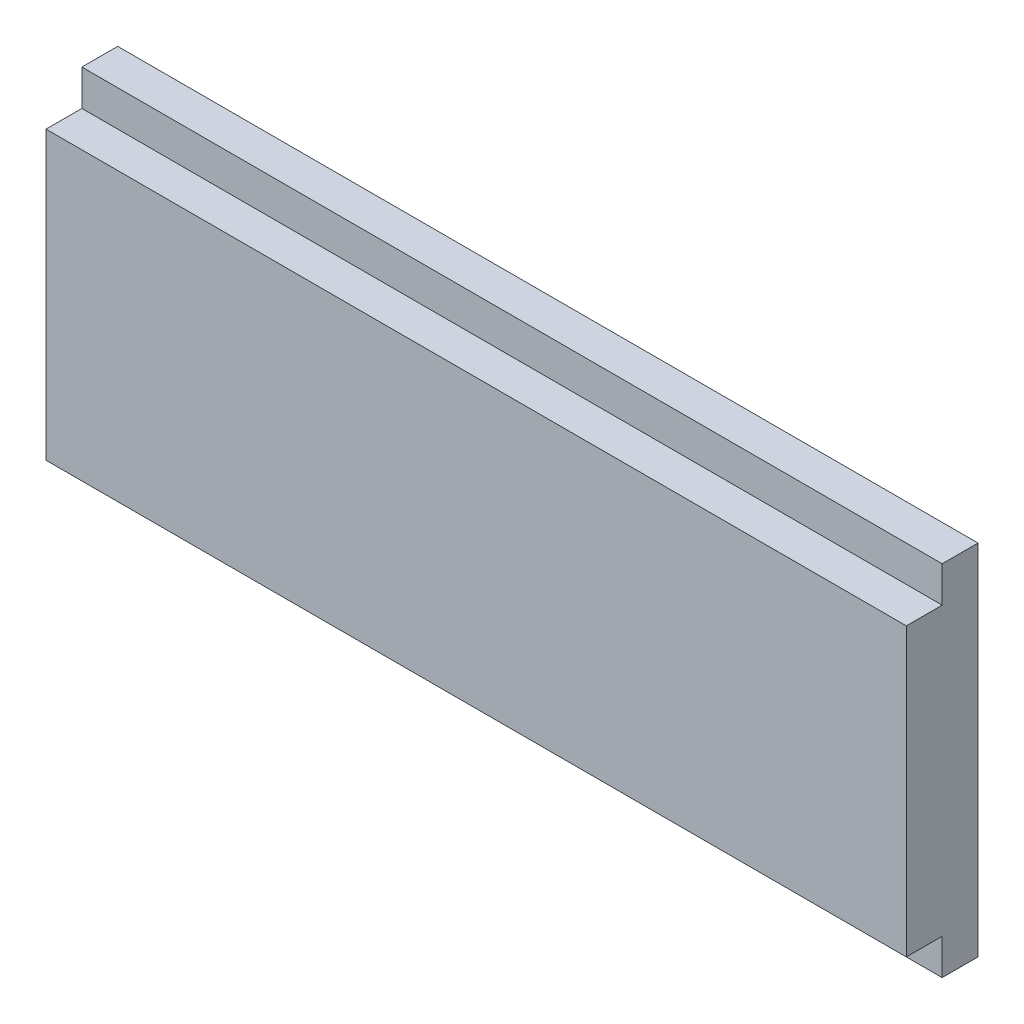
SolidWorks part; units mm, degrees
ref_plane "Спереди" through (0, 0, 0) normal (0, 0, 1) x (1, 0, 0)
ref_plane "Сверху" through (0, 0, 0) normal (0, 1, 0) x (1, 0, 0)
ref_plane "Справа" through (0, 0, 0) normal (1, 0, 0) x (0, 0, -1)
other "Configuration Table"
sketch "Эскиз1" plane through (0, 0, 0) normal (0, 0, 1) x (1, 0, 0)
  line L1 (30, -12.5) -> (-30, -12.5)
  line L2 (30, -12.5) -> (30, 12.5)
  line L3 (30, 12.5) -> (-30, 12.5)
  line L4 (-30, -12.5) -> (-30, 12.5)
  line L5 (30, -12.5) -> (-30, 12.5) construction
  line L6 (30, 12.5) -> (-30, -12.5) construction
  point P0 (0, 0)
  dimension "D1" = 60
  dimension "D2" = 25
extrude "Бобышка-Вытянуть1" add sketch "Эскиз1" along normal blind 2.5
sketch "Эскиз2" plane through (0, 0, 2.5) normal (0, 0, 1) x (1, 0, 0)
  line L0 (-30, 10) -> (30, 10)
  line L1 (-30, 12.5) -> (-30, -12.5) construction
  line L2 (30, -12.5) -> (30, 12.5) construction
  line L3 (30, -10) -> (-30, -10)
  line L4 (30, 12.5) -> (-30, 12.5) construction
  line L5 (-30, -12.5) -> (30, -12.5) construction
  line L6 (-30, 10) -> (-30, -10)
  line L7 (30, 10) -> (30, -10)
  dimension "D1" = 2.5
  dimension "D2" = 2.5
extrude "Бобышка-Вытянуть2" add sketch "Эскиз2" along normal blind 2.5
